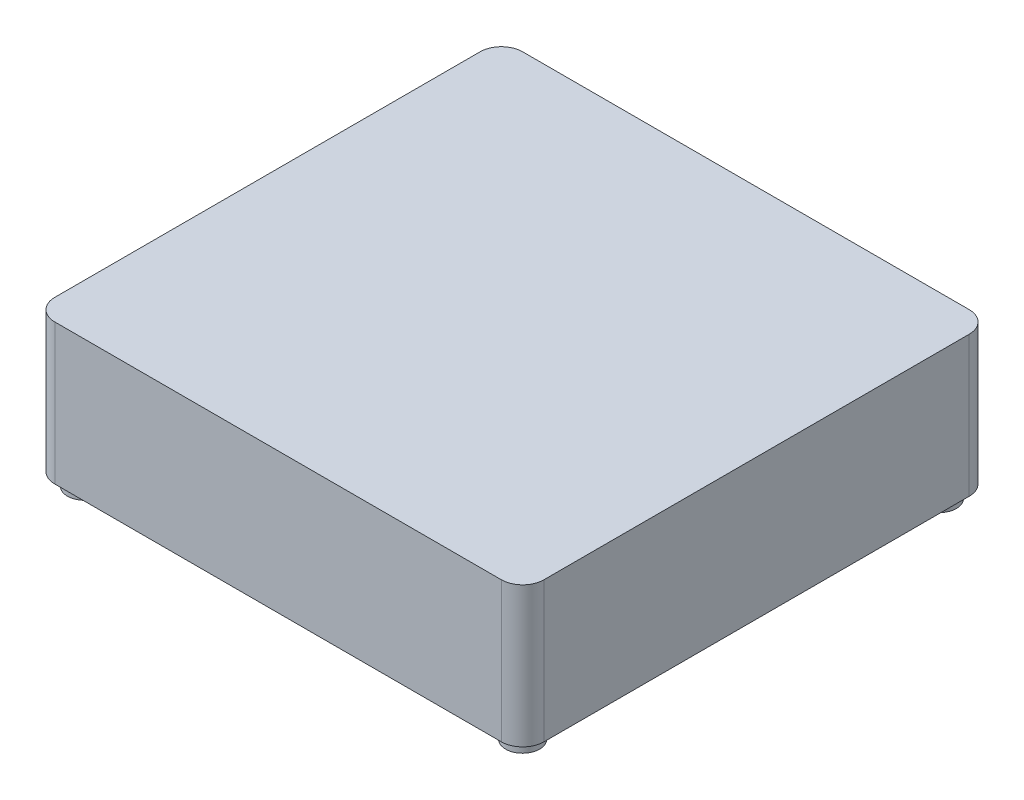
SolidWorks part; units mm, degrees
ref_plane "前视基准面" through (0, 0, 0) normal (0, 0, 1) x (1, 0, 0)
ref_plane "上视基准面" through (0, 0, 0) normal (0, 1, 0) x (1, 0, 0)
ref_plane "右视基准面" through (0, 0, 0) normal (1, 0, 0) x (0, 0, -1)
sketch "草图1" plane through (0, 0, 0) normal (0, 1, 0) x (1, 0, 0)
  line L1 (-52.5, 55) -> (52.5, 55)
  line L2 (-57.5, 50) -> (-57.5, -50)
  line L3 (-52.5, -55) -> (52.5, -55)
  line L4 (57.5, 50) -> (57.5, -50)
  line L5 (-57.5, 55) -> (57.5, -55) construction
  line L6 (-57.5, -55) -> (57.5, 55) construction
  arc A0 (-57.5, 50) -> (-52.5, 55) centre (-52.5, 50) cw
  arc A1 (-57.5, -50) -> (-52.5, -55) centre (-52.5, -50) ccw
  arc A2 (52.5, -55) -> (57.5, -50) centre (52.5, -50) ccw
  arc A3 (57.5, 50) -> (52.5, 55) centre (52.5, 50) ccw
  point P0 (0, 0)
  dimension "D3" = 5
  dimension "D4" = 5
  dimension "D1" = 110
  dimension "D2" = 115
extrude "凸台-拉伸1" add sketch "草图1" along normal blind 33
sketch "草图2" plane through (0, 0, 0) normal (0, -1, 0) x (1, 0, 0)
  line L0 (0, 57.8381) -> (0, -57.7673) construction
  line L1 (-67.5662, 0) -> (73.9337, 0) construction
  line L2 (-52.5, 55) -> (52.5, 55) construction
  line L3 (-57.5, -50) -> (-57.5, 50) construction
  line L4 (57.5, 50) -> (57.5, -50) construction
  line L5 (52.5, -55) -> (-52.5, -55) construction
  circle A0 centre (-51.5, 49) radius 4
  circle A1 centre (51.5, 49) radius 4
  circle A2 centre (-51.5, -49) radius 4
  circle A3 centre (51.5, -49) radius 4
  point P13 (0, 0)
  point P14 (0, 0)
  point P15 (0, 0)
  point P16 (0, 0)
  dimension "D1" = 8
  dimension "D2" = 6
  dimension "D3" = 6
  dimension "D4" = 6
  dimension "D5" = 6
extrude "凸台-拉伸2" add sketch "草图2" along normal blind 3
sketch "草图3" plane through (0, 0, -55) normal (0, 0, -1) x (-1, 0, 0)
  line L0 (-52.5, 0) -> (52.5, 0) construction
  line L1 (29.5, 15) -> (39.5, 15)
  line L2 (29.5, 15) -> (29.5, 5)
  line L3 (29.5, 5) -> (39.5, 5)
  line L4 (39.5, 15) -> (39.5, 5)
  line L5 (29.5, 15) -> (39.5, 5) construction
  line L6 (29.5, 5) -> (39.5, 15) construction
  line L7 (57.5, 33) -> (57.5, 0) construction
  line L9 (30, 14.5) -> (39, 14.5)
  line L10 (30, 14.5) -> (30, 5.5)
  line L11 (30, 5.5) -> (39, 5.5)
  line L12 (39, 14.5) -> (39, 5.5)
  line L13 (30, 14.5) -> (39, 5.5) construction
  line L14 (30, 5.5) -> (39, 14.5) construction
  point P0 (34.5, 10)
  point P9 (34.5, 10)
  dimension "D1" = 10
  dimension "D2" = 10
  dimension "D3" = 5
  dimension "D4" = 18
  dimension "D5" = 0.5
extrude "切除-拉伸1" cut sketch "草图3" against normal blind 5
sketch "草图4" plane through (0, 0, -55) normal (0, 0, -1) x (-1, 0, 0)
  line L1 (30, 14.5) -> (39, 5.5) construction
  line L2 (39, 14.5) -> (30, 5.5) construction
  circle A0 centre (34.5, 10) radius 3
  circle A1 centre (34.5, 10) radius 3.1
  dimension "D1" = 6
  dimension "D2" = 6.2
extrude "切除-拉伸2" cut sketch "草图4" against normal blind 10
